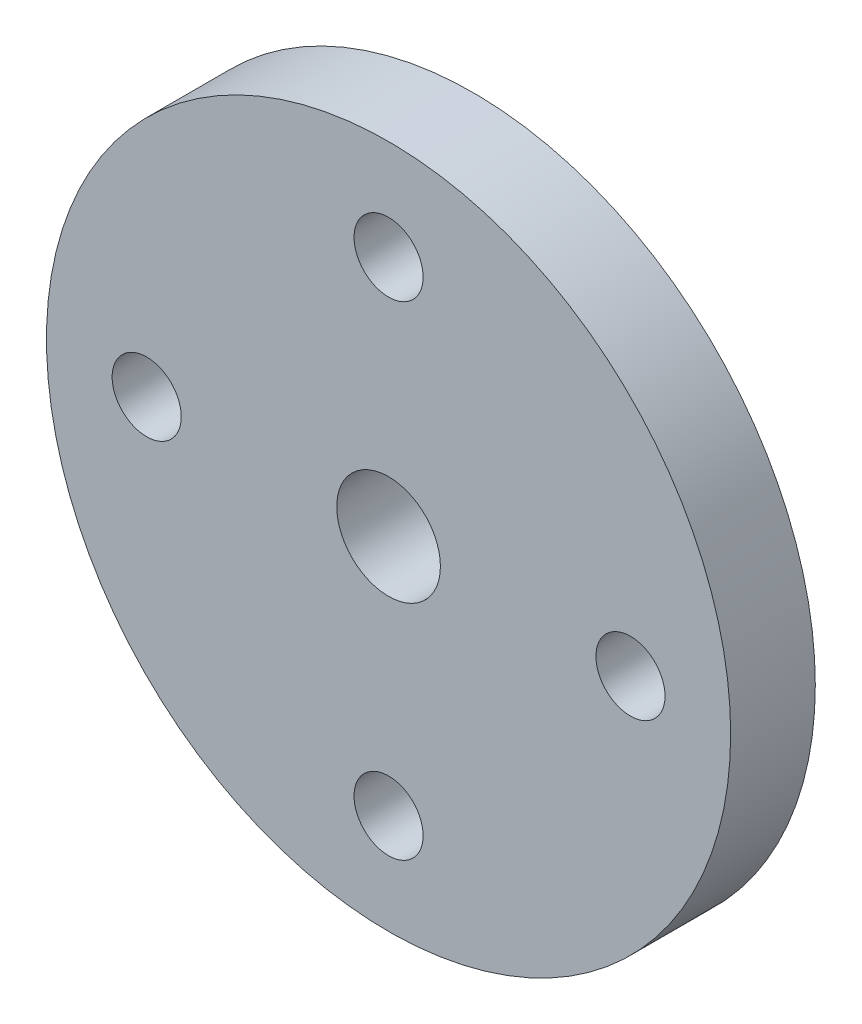
SolidWorks part; units mm, degrees
ref_plane "Alzado" through (0, 0, 0) normal (0, 0, 1) x (1, 0, 0)
ref_plane "Planta" through (0, 0, 0) normal (0, 1, 0) x (1, 0, 0)
ref_plane "Vista lateral" through (0, 0, 0) normal (1, 0, 0) x (0, 0, -1)
sketch "Croquis1" plane through (0, 0, 0) normal (0, 0, 1) x (1, 0, 0)
  circle A0 centre (0, 0) radius 9.9
  dimension "D1" = 19.8
extrude "Saliente-Extruir1" add sketch "Croquis1" along normal blind 2.45
sketch "Croquis2" plane through (0, 0, 2.45) normal (0, 0, 1) x (1, 0, 0)
  circle A0 centre (0, 0) radius 4.5
  dimension "D1" = 9
extrude "Saliente-Extruir2" add sketch "Croquis2" against normal blind 4.5
sketch "Croquis3" plane through (0, 0, 2.45) normal (0, 0, 1) x (1, 0, 0)
  line L0 (0, 0) -> (7, 0) construction
  circle A0 centre (0, 0) radius 1.5
  circle A1 centre (7, 0) radius 1
  circle A2 centre (0, -7) radius 1
  circle A3 centre (-7, 0) radius 1
  circle A4 centre (0, 7) radius 1
  point P14 (0, 0)
  dimension "D1" = 3
  dimension "D2" = 2
  dimension "D3" = 7
  dimension "D4" = 4
extrude "Cortar-Extruir1" cut sketch "Croquis3" against normal through all
